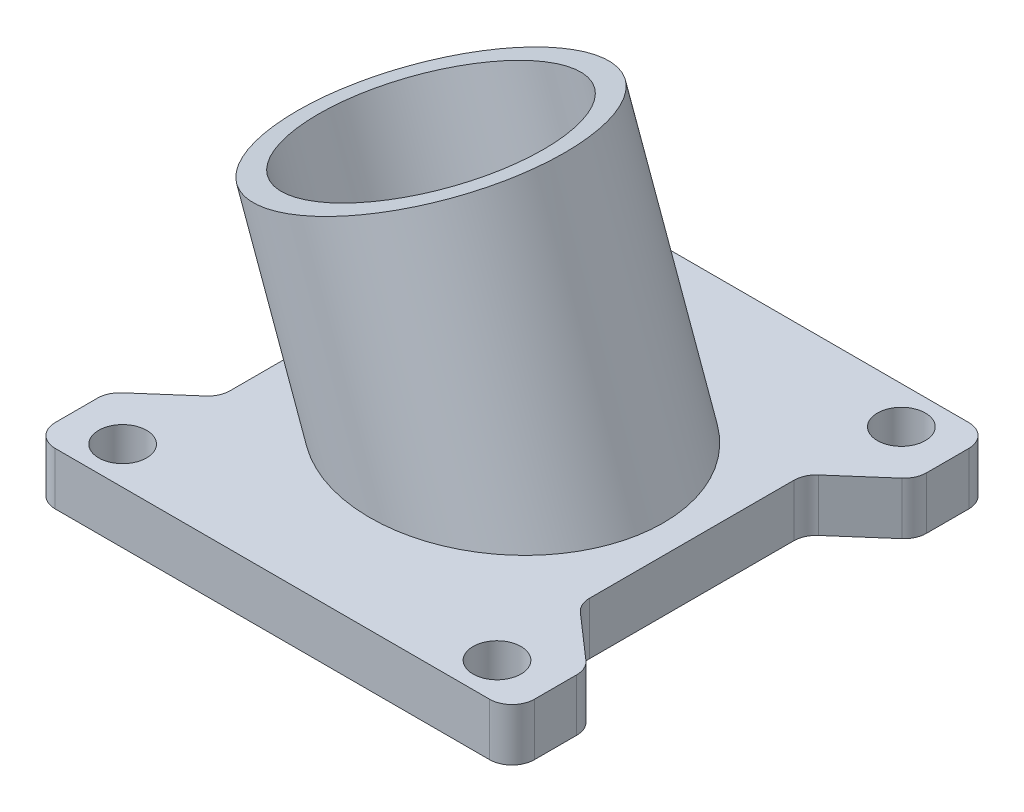
SolidWorks part; units mm, degrees
ref_plane "Front Plane" through (0, 0, 0) normal (0, 0, 1) x (1, 0, 0)
ref_plane "Top Plane" through (0, 0, 0) normal (0, 1, 0) x (1, 0, 0)
ref_plane "Right Plane" through (0, 0, 0) normal (1, 0, 0) x (0, 0, -1)
sketch "Sketch1" plane through (0, 0, 0) normal (0, 1, 0) x (1, 0, 0)
  line L0 (-12, 0) -> (-12, 7.5)
  line L1 (-12, 7.5) -> (-16, 11)
  line L2 (-16, 11) -> (-16, 16)
  line L3 (-16, 16) -> (16, 16)
  line L8 (-12, 0) -> (12, 0)
  line L9 (0, 16) -> (0, 0) construction
  line L10 (16, 11) -> (16, 16)
  line L11 (12, 7.5) -> (16, 11)
  line L12 (12, 0) -> (12, 7.5)
  point P9 (0, 0)
  point P11 (-17, 12.4694)
  point P12 (0, 0)
  point P13 (0, 0)
  point P16 (0, 0)
  point P17 (-11.4719, 7.5)
  dimension "D1" = 32
  dimension "D2" = 16
  dimension "D3" = 5
  dimension "D4" = 7.5
  dimension "D5" = 24
extrude "Boss-Extrude1" add sketch "Sketch1" along normal blind 3.5
sketch "Sketch2" plane through (0, 3.5, 0) normal (0, 1, 0) x (1, 0, 0)
  line L0 (-16, 13.5) -> (16, 13.5) construction
  line L1 (-16, 16) -> (-16, 11) construction
  line L2 (16, 11) -> (16, 16) construction
  line L3 (0, 0) -> (0, 16) construction
  line L4 (-12, 0) -> (12, 0) construction
  line L5 (16, 16) -> (-16, 16) construction
  circle A0 centre (-12.5, 13.5) radius 1.6
  circle A2 centre (12.5, 13.5) radius 1.6
  dimension "D1" = 3.2
  dimension "D2" = 12.5
extrude "Cut-Extrude1" cut sketch "Sketch2" against normal up to next
fillet "Fillet1" radius 1.5 6 edges at (12, 1.75, -7.5) (16, 1.75, -11) (16, 1.75, -16) (-12, 1.75, -7.5) (-16, 1.75, -11) (-16, 1.75, -16)
mirror "Mirror1" about plane through (0, 0, 0) normal (0, 0, 1) of "Fillet1", "Cut-Extrude1", "Boss-Extrude1"
ref_plane "Plane2" through (-1.4037, 3.8567, 0) normal (-0.342, 0.9397, 0) x (0, 0, 1)
sketch "Sketch3" plane through (-1.4037, 3.8567, 0) normal (-0.342, 0.9397, 0) x (0, 0, 1)
  line L1 (-16, 1.1971) -> (16, 1.1971) construction
  line L2 (-16, 14.8226) -> (-16, -12.4285) construction
  line L3 (16, 14.8226) -> (16, -12.4285) construction
  circle A0 centre (0, 1.1971) radius 8
  circle A1 centre (0, 1.1971) radius 9.5
  point P4 (0, 1.1971)
  point P5 (0, 0)
  dimension "D1" = 16
  dimension "D2" = 1.5
extrude "Boss-Extrude3" add sketch "Sketch3" along normal blind 15 and the other way up to surface other way up to face at (-12.5, 3.5, 11.9)
